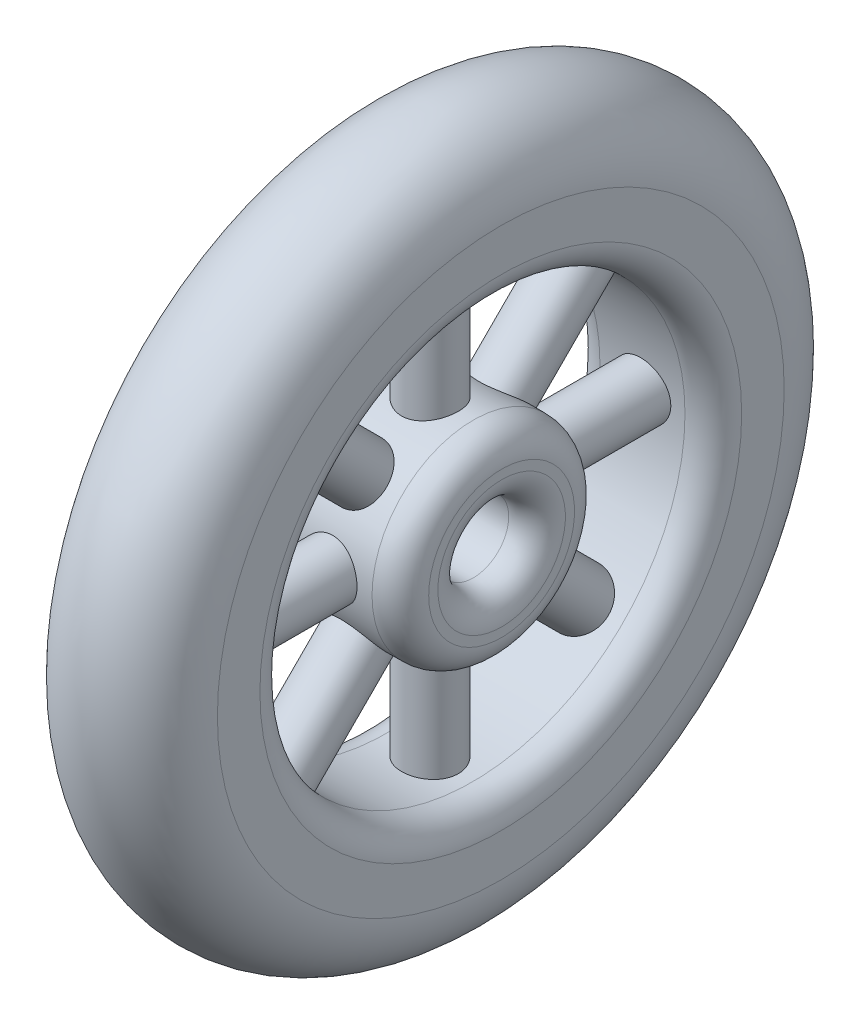
SolidWorks part; units mm, degrees
material "ABS"
ref_plane "Front Plane" through (0, 0, 0) normal (0, 0, 1) x (1, 0, 0)
ref_plane "Top Plane" through (0, 0, 0) normal (0, 1, 0) x (1, 0, 0)
ref_plane "Right Plane" through (0, 0, 0) normal (1, 0, 0) x (0, 0, -1)
sketch "Sketch3" plane through (0, 0, 0) normal (0, 0, 1) x (1, 0, 0)
  line L2 (13.3734, 0) -> (-13.3734, 0) construction
  line L4 (0, 1.5875) -> (0, 15.875) construction
  line L5 (-1.9422, 1.5875) -> (1.9422, 1.5875)
  line L6 (1.9422, 4.5382) -> (-1.9422, 4.5382)
  line L7 (0, -8.7312) -> (0, 8.7312) construction
  line L8 (-11.9772, 0) -> (12.3381, 0) construction
  line L11 (3.2122, 2.8575) -> (3.2122, 3.2682)
  line L13 (-3.2122, 2.8575) -> (-3.2122, 3.2682)
  line L14 (-3.175, 12.7) -> (-3.175, 10.795)
  line L15 (-1.905, 9.525) -> (1.905, 9.525)
  line L16 (3.175, 10.795) -> (3.175, 12.7)
  arc A0 (3.175, 12.7) -> (-3.175, 12.7) centre (0, 12.7) ccw
  arc A1 (1.905, 9.525) -> (3.175, 10.795) centre (1.905, 10.795) ccw
  arc A2 (-1.905, 9.525) -> (-3.175, 10.795) centre (-1.905, 10.795) cw
  arc A3 (-3.2122, 2.8575) -> (-1.9422, 1.5875) centre (-1.9422, 2.8575) ccw
  arc A4 (-3.2122, 3.2682) -> (-1.9422, 4.5382) centre (-1.9422, 3.2682) cw
  arc A5 (3.2122, 2.8575) -> (1.9422, 1.5875) centre (1.9422, 2.8575) cw
  arc A6 (3.2122, 3.2682) -> (1.9422, 4.5382) centre (1.9422, 3.2682) ccw
  dimension "D1" = 6.35
  dimension "D2" = 1.27
  dimension "D3" = 1.27
  dimension "D4" = 3.2122
  dimension "D5" = 1.5875
  dimension "D6" = 4.5382
  dimension "D7" = 15.875
revolve "Revolve1" add sketch "Sketch3" angle 360 about L8
sketch "Sketch5" plane through (0, 0, 0) normal (1, 0, 0) x (0, 0, -1)
  line L0 (0, 3.0628) -> (0, 12.7)
  line L1 (0, 2.8575) -> (0, 3.2682) construction
sweep "Sweep1" add path "Sketch5" circular profile diameter 2.54 parameters "D3"=2.54
pattern_circular "CirPattern1" count 8 over 360 about axis through (-11.9772, 0, 0) along (1, 0, 0) of "Sweep1"
scale "Scale" scale about centroid uniform scaling yes scale factor 1.15
